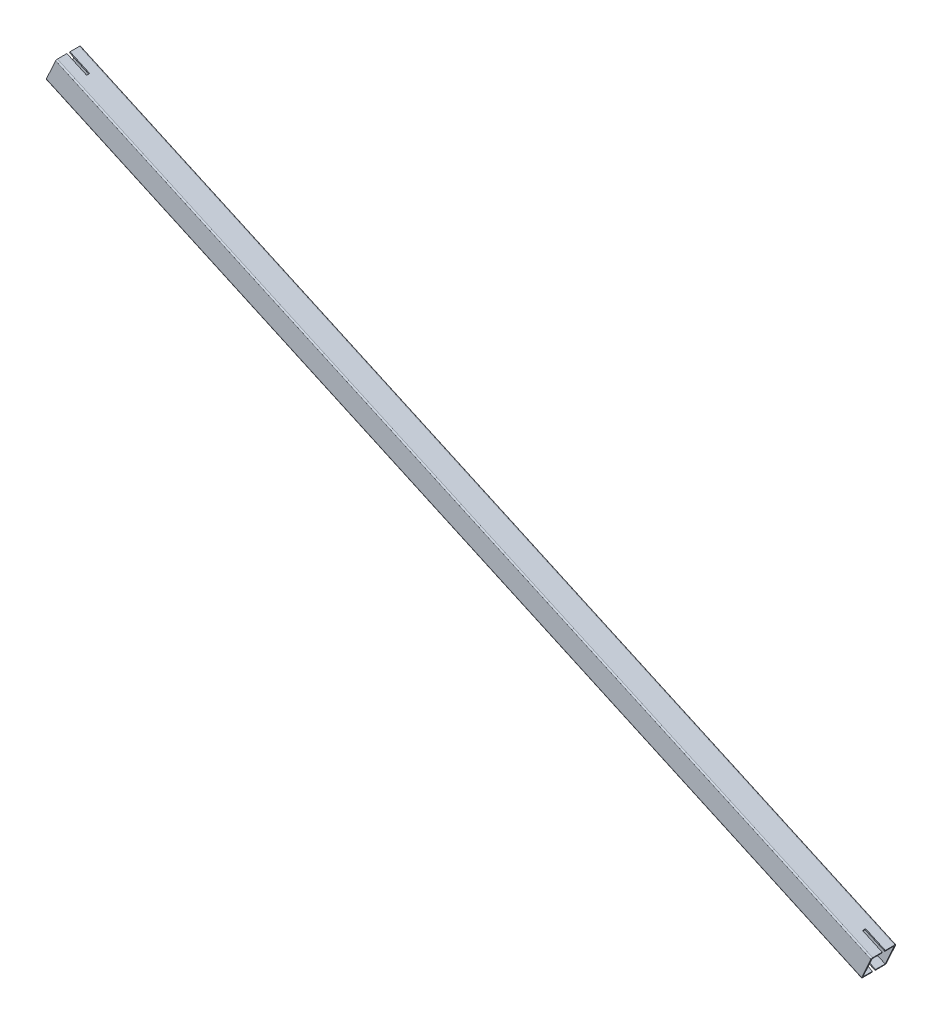
SolidWorks part; units mm, degrees
material "Простая углеродистая сталь"
ref_plane "Спереди" through (0, 0, 0) normal (0, 0, 1) x (1, 0, 0)
ref_plane "Сверху" through (0, 0, 0) normal (0, 1, 0) x (1, 0, 0)
ref_plane "Справа" through (0, 0, 0) normal (1, 0, 0) x (0, 0, -1)
sketch "Эскиз1" plane through (0, 0, 0) normal (0, 0, 1) x (1, 0, 0)
  line L0 (0, 0) -> (2640.0628, -1200.0285)
  line L1 (0, 0) -> (5280.1256, 0) construction
  line L2 (0, 0) -> (0, -2400.0571) construction
  line L3 (0, -2400.0571) -> (5280.1256, -2400.0571) construction
  line L4 (5280.1256, 0) -> (5280.1256, -2400.0571) construction
  line L5 (5280.1256, 0) -> (0, -2400.0571) construction
  line L6 (5280.1256, -2400.0571) -> (0, 0) construction
  dimension "D1" = 2900
  dimension "D2" = 65.556
other "Квадратная труба гост 8639-82 _80 X 80 X 4.0(1)"
ref_plane "Плоскость1" through (0, 0, 0) normal (0.9104, -0.4138, 0) x (0.4138, 0.9104, 0)
sketch "Sketch11" plane through (0, 0, 0) normal (0.9104, -0.4138, 0) x (0.4138, 0.9104, 0)
  line L0 (-35.999, -36) -> (35.999, -36)
  line L1 (-36, -35.999) -> (-36, 35.999)
  line L2 (35.999, 36) -> (-35.999, 36)
  line L3 (36, 35.999) -> (36, -35.999)
  line L4 (-35.999, -40) -> (35.999, -40)
  line L5 (-40, -35.999) -> (-40, 35.999)
  line L6 (35.999, 40) -> (-35.999, 40)
  line L7 (40, 35.999) -> (40, -35.999)
  arc A0 (40, 35.999) -> (35.999, 40) centre (35.999, 35.999) ccw
  arc A1 (35.999, -40) -> (40, -35.999) centre (35.999, -35.999) ccw
  arc A2 (-40, -35.999) -> (-35.999, -40) centre (-35.999, -35.999) ccw
  arc A3 (-35.999, 40) -> (-40, 35.999) centre (-35.999, 35.999) ccw
  arc A4 (-35.999, 36) -> (-36, 35.999) centre (-35.999, 35.999) ccw
  arc A5 (36, 35.999) -> (35.999, 36) centre (35.999, 35.999) ccw
  arc A6 (35.999, -36) -> (36, -35.999) centre (35.999, -35.999) ccw
  arc A7 (-36, -35.999) -> (-35.999, -36) centre (-35.999, -35.999) ccw
  point P0 (-40, 0)
  point P1 (40, 0)
  point P2 (0, 40)
  point P3 (0, -40)
  point P4 (0, 0)
  point P5 (-40, -40)
  point P6 (40, -40)
  point P7 (40, 40)
  point P8 (-40, 40)
  point P33 (0, 0)
  dimension "D1" = 4.001
  dimension "Thickness" = 4
  dimension "V_leg" = 80
sketch "Эскиз3" plane through (-16.5521, -36.4147, 0) normal (-0.4138, -0.9104, 0) x (0.9104, -0.4138, 0)
  line L0 (0, 0) -> (40.9414, 0) construction
  line L1 (0, 35.999) -> (0, -35.999) construction
  line L2 (0, 5) -> (70, 5)
  line L3 (0, 5) -> (0, -5)
  line L4 (0, -5) -> (70, -5)
  line L5 (70, 5) -> (70, -5)
  line L6 (2900, 0) -> (4923.0006, 0) construction
  line L7 (2900, 35.999) -> (2900, -35.999) construction
  line L9 (2900, 5) -> (2830, 5)
  line L10 (2900, 5) -> (2900, -5)
  line L11 (2900, -5) -> (2830, -5)
  line L12 (2830, 5) -> (2830, -5)
  dimension "D1" = 70
  dimension "D2" = 10
extrude "Вырез-Вытянуть1" cut sketch "Эскиз3" against normal through all
sketch "Эскиз4" [suppressed] plane through (1426.9754, -1934.8819, -2404.1686) normal (-0.5935, 0.8048, 0) x (-0.6477, -0.4777, -0.5935)
  line L0 (0, 0) -> (40.9414, 0) construction
  line L2 (0, 3) -> (40, 3)
  line L3 (0, 3) -> (0, -3)
  line L4 (0, -3) -> (40, -3)
  line L5 (40, 3) -> (40, -3)
  line L6 (4970.161, 0) -> (4923.0006, 0) construction
  line L9 (4970.161, 3) -> (4930.161, 3)
  line L10 (4970.161, 3) -> (4970.161, -3)
  line L11 (4970.161, -3) -> (4930.161, -3)
  line L12 (4930.161, 3) -> (4930.161, -3)
  dimension "D1" = 40
  dimension "D2" = 6
equation "\"D1@Sketch11\" = \"Thickness@Sketch11\"+0.001"
